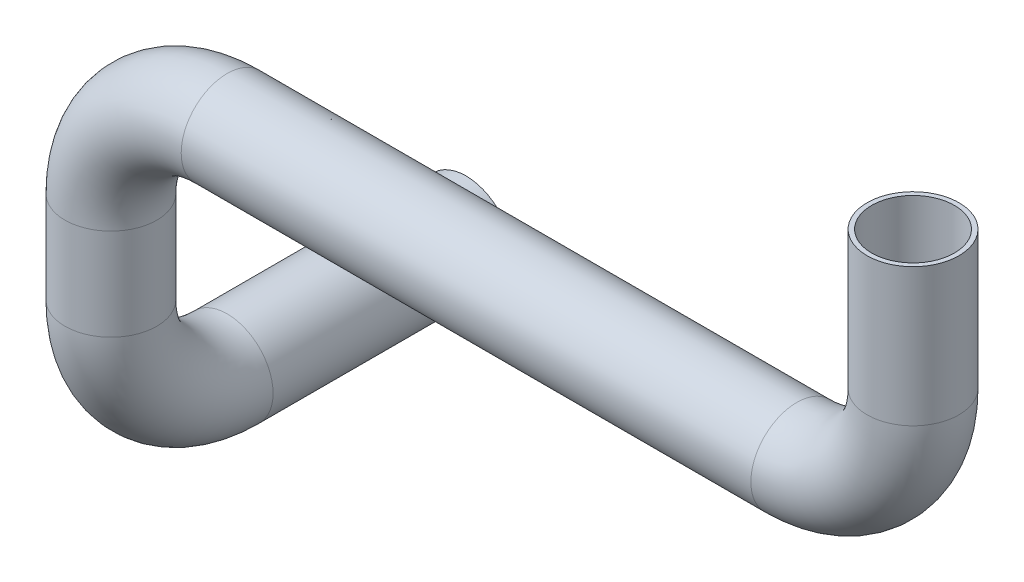
SolidWorks part; units mm, degrees
material "201 Annealed Stainless Steel (SS)"
ref_plane "Front Plane" through (0, 0, 0) normal (0, 0, 1) x (1, 0, 0)
ref_plane "Top Plane" through (0, 0, 0) normal (0, 1, 0) x (1, 0, 0)
ref_plane "Right Plane" through (0, 0, 0) normal (1, 0, 0) x (0, 0, -1)
sketch "Sketch1" plane through (0, 0, 0) normal (0, 1, 0) x (1, 0, 0)
  circle A0 centre (0, 0) radius 5
  dimension "D1" = 10
sketch "Sketch2" plane through (0, 0, 0) normal (0, 0, 1) x (1, 0, 0)
  line L0 (0, 0) -> (0, 10)
  line L1 (12.65, 22.65) -> (74.65, 22.65)
  line L2 (87.3, 35.3) -> (87.3, 50.3)
  arc A0 (74.65, 22.65) -> (87.3, 35.3) centre (74.65, 35.3) ccw
  arc A1 (0, 10) -> (12.65, 22.65) centre (12.65, 10) cw
  point P9 (0, 13.4311)
  point P10 (54.3891, 47.5766)
  point P11 (54.7657, 55.3639)
  dimension "D1" = 12.65
  dimension "D2" = 10
  dimension "D3" = 15
  dimension "D4" = 62
sweep "Sweep1" add profiles "Sketch1" path "Sketch2"
sketch "Sketch3" plane through (0, 0, 0) normal (0, -1, 0) x (1, 0, 0)
  circle A1 centre (0, 0) radius 5
  circle A2 centre (0, 0) radius 5
  dimension "D1" = 0
sketch "Sketch5" plane through (0, 0, 0) normal (1, 0, 0) x (0, 0, -1)
  line L0 (12.65, -12.65) -> (38.65, -12.65)
  arc A0 (0, 0) -> (12.65, -12.65) centre (12.65, 0) ccw
  point P3 (0, 0)
  point P8 (0, 0)
  dimension "D2" = 12.65
  dimension "D1" = 26
sweep "Sweep2" add profiles "Sketch3" path "Sketch5"
shell "Shell1" thickness 0.5
